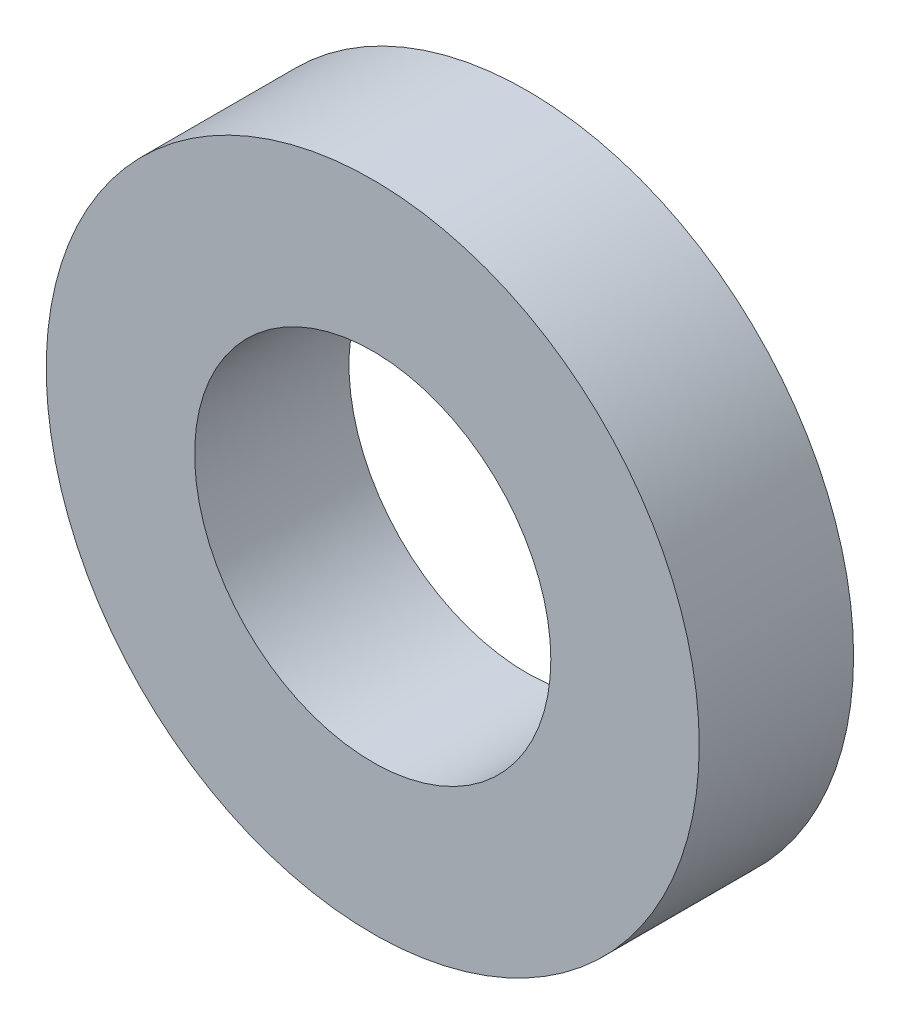
SolidWorks part; units mm, degrees
ref_plane "Front Plane" through (0, 0, 0) normal (0, 0, 1) x (1, 0, 0)
ref_plane "Top Plane" through (0, 0, 0) normal (0, 1, 0) x (1, 0, 0)
ref_plane "Right Plane" through (0, 0, 0) normal (1, 0, 0) x (0, 0, -1)
sketch "Sketch1" plane through (0, 0, 0) normal (0, 0, 1) x (1, 0, 0)
  circle A0 centre (0, 0) radius 15
  circle A1 centre (0, 0) radius 27.5
  dimension "D1" = 55
  dimension "D2" = 30
extrude "Boss-Extrude1" add sketch "Sketch1" against normal blind 13
